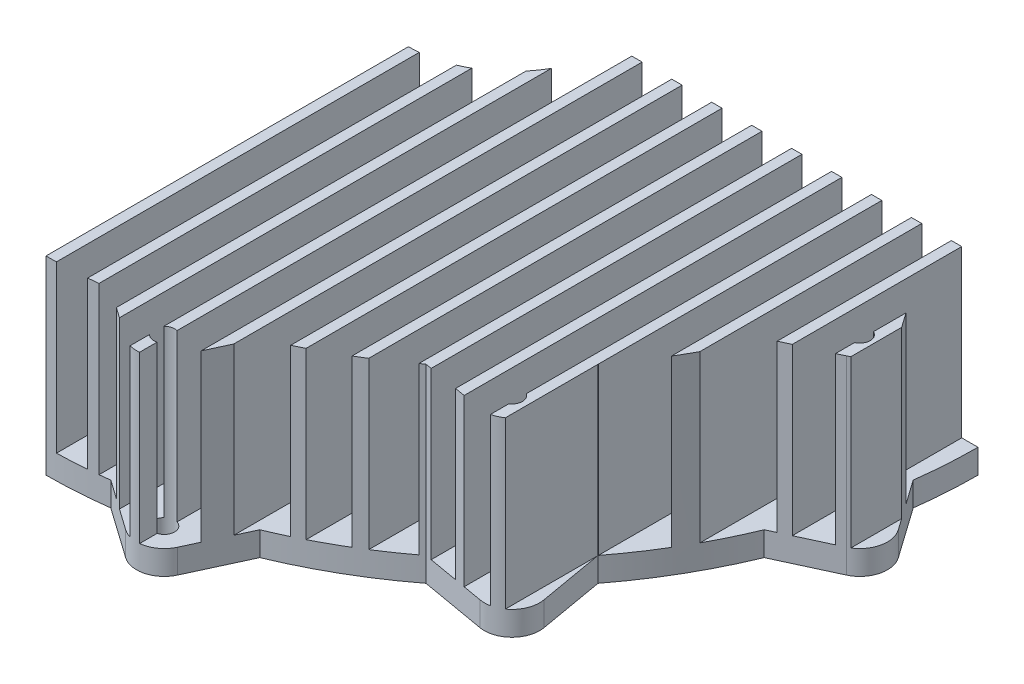
SolidWorks part; units mm, degrees
ref_plane "Ön Düzlem" through (0, 0, 0) normal (0, 0, 1) x (1, 0, 0)
ref_plane "Üst Düzlem" through (0, 0, 0) normal (0, 1, 0) x (1, 0, 0)
ref_plane "Sağ Düzlem" through (0, 0, 0) normal (1, 0, 0) x (0, 0, -1)
sketch "Sketch1" plane through (0, 0, 0) normal (0, 0, 1) x (1, 0, 0)
  line L0 (11.5714, 7) -> (11.5714, 55)
  line L1 (0, 0) -> (165, 0)
  line L2 (0, 0) -> (0, 7)
  line L3 (3, 7) -> (11.5714, 7)
  line L4 (165, 0) -> (165, 10)
  line L6 (0, 7) -> (0, 55)
  line L7 (0, 55) -> (3, 55)
  line L8 (3, 7) -> (3, 55)
  line L10 (14.5714, 7) -> (14.5714, 55)
  line L11 (11.5714, 55) -> (14.5714, 55)
  line L12 (23.1429, 7) -> (23.1429, 55)
  line L14 (26.1429, 7) -> (26.1429, 55)
  line L15 (23.1429, 55) -> (26.1429, 55)
  line L16 (34.7143, 7) -> (34.7143, 55)
  line L18 (37.7143, 7) -> (37.7143, 55)
  line L19 (34.7143, 55) -> (37.7143, 55)
  line L20 (46.2857, 7) -> (46.2857, 55)
  line L22 (49.2857, 7) -> (49.2857, 55)
  line L23 (46.2857, 55) -> (49.2857, 55)
  line L24 (57.8571, 7) -> (57.8571, 55)
  line L26 (60.8571, 7) -> (60.8571, 55)
  line L27 (57.8571, 55) -> (60.8571, 55)
  line L28 (69.4286, 7) -> (69.4286, 55)
  line L30 (72.4286, 7) -> (72.4286, 55)
  line L31 (69.4286, 55) -> (72.4286, 55)
  line L32 (81, 7) -> (81, 55)
  line L34 (84, 7) -> (84, 55)
  line L35 (81, 55) -> (84, 55)
  line L36 (92.5714, 7) -> (92.5714, 55)
  line L38 (95.5714, 7) -> (95.5714, 55)
  line L39 (92.5714, 55) -> (95.5714, 55)
  line L40 (104.1429, 7) -> (104.1429, 55)
  line L42 (107.1429, 7) -> (107.1429, 55)
  line L43 (104.1429, 55) -> (107.1429, 55)
  line L44 (115.7143, 7) -> (115.7143, 55)
  line L46 (118.7143, 7) -> (118.7143, 55)
  line L47 (115.7143, 55) -> (118.7143, 55)
  line L48 (127.2857, 7) -> (127.2857, 55)
  line L50 (130.2857, 7) -> (130.2857, 55)
  line L51 (127.2857, 55) -> (130.2857, 55)
  line L52 (138.8571, 7) -> (138.8571, 55)
  line L54 (141.8571, 7) -> (141.8571, 55)
  line L55 (138.8571, 55) -> (141.8571, 55)
  line L56 (150.4286, 7) -> (150.4286, 55)
  line L58 (153.4286, 7) -> (153.4286, 55)
  line L59 (150.4286, 55) -> (153.4286, 55)
  line L60 (162, 7) -> (162, 55)
  line L62 (165, 7) -> (165, 55)
  line L63 (162, 55) -> (165, 55)
  line L78 (14.5714, 7) -> (23.1429, 7)
  line L79 (26.1429, 7) -> (34.7143, 7)
  line L80 (37.7143, 7) -> (46.2857, 7)
  line L81 (49.2857, 7) -> (57.8571, 7)
  line L82 (60.8571, 7) -> (69.4286, 7)
  line L83 (72.4286, 7) -> (81, 7)
  line L84 (84, 7) -> (92.5714, 7)
  line L85 (95.5714, 7) -> (104.1429, 7)
  line L86 (107.1429, 7) -> (115.7143, 7)
  line L87 (118.7143, 7) -> (127.2857, 7)
  line L88 (130.2857, 7) -> (138.8571, 7)
  line L89 (141.8571, 7) -> (150.4286, 7)
  line L90 (153.4286, 7) -> (162, 7)
  dimension "D1" = 165
  dimension "D2" = 7
  dimension "D3" = 48
  dimension "D4" = 3
  dimension "D5" = 15
extrude "Boss-Extrude1" add sketch "Sketch1" along normal blind 1000 contours L90 L58 L59 L56 L89 L54 L55 L52 L88 L50 L51 L48 L87 L46 L47 L44 L86 L42 L43 L40 L85 L38 L39 L36 L84 L34 L35 L32 L83 L30 L31 L28 L82 L26 L27 L24 L81 L22 L23 L20 L80 L18 L19 L16 L79 L14 L15 L12 L78 L10 L11
sketch "Sketch2" plane through (0, 0, 0) normal (0, -1, 0) x (1, 0, 0)
  line L0 (0, 142.5) -> (0, 0)
  line L1 (0, 0) -> (142.5, 0)
  line L2 (0, 0) -> (102.5305, 102.5305) construction
  line L3 (0, 0) -> (36.8817, 137.6444) construction
  line L4 (0, 0) -> (137.6444, 36.8817) construction
  line L5 (0, 0) -> (17.621, 133.8451)
  line L6 (0, 0) -> (51.6623, 124.7237)
  line L7 (0, 0) -> (82.1828, 107.1027)
  line L8 (0, 0) -> (107.1027, 82.1828)
  line L9 (0, 0) -> (124.7237, 51.6623)
  line L10 (0, 0) -> (133.8451, 17.621)
  line L11 (17.621, 133.8451) -> (32.2695, 144.181)
  line L12 (51.6623, 124.7237) -> (44.1443, 140.9992)
  line L13 (82.1828, 107.1027) -> (101.1561, 110.4115)
  line L14 (107.1027, 82.1828) -> (110.4115, 101.1561)
  line L15 (124.7237, 51.6623) -> (140.9992, 44.1443)
  line L16 (133.8451, 17.621) -> (144.181, 32.2695)
  arc A0 (135, 0) -> (133.8451, 17.621) centre (0, 0) ccw
  circle A2 centre (36.8817, 137.6444) radius 3
  circle A3 centre (102.5305, 102.5305) radius 3
  circle A4 centre (137.6444, 36.8817) radius 3
  arc A5 (44.1443, 140.9992) -> (32.2695, 144.181) centre (36.8817, 137.6444) ccw
  arc A6 (110.4115, 101.1561) -> (101.1561, 110.4115) centre (102.5305, 102.5305) ccw
  arc A7 (144.181, 32.2695) -> (140.9992, 44.1443) centre (137.6444, 36.8817) ccw
  arc A9 (101.9184, 99.5936) -> (99.5936, 101.9184) centre (0, 0) ccw
  arc A12 (138.3903, 33.9759) -> (136.8375, 39.7712) centre (0, 0) ccw
  arc A13 (17.621, 133.8451) -> (0, 135) centre (0, 0) ccw
  arc A14 (82.1828, 107.1027) -> (51.6623, 124.7237) centre (0, 0) ccw
  arc A15 (124.7237, 51.6623) -> (107.1027, 82.1828) centre (0, 0) ccw
  dimension "D1" = 270
  dimension "D3" = 6
  dimension "D4" = 6
  dimension "D5" = 6
  dimension "D8" = 16
  dimension "D9" = 16
  dimension "D10" = 16
  dimension "D6" = 15
  dimension "D7" = 15
  dimension "D11" = 45
  dimension "D12" = 7.5
  dimension "D13" = 7.5
  dimension "D14" = 7.5
  dimension "D15" = 7.5
  dimension "D16" = 7.5
  dimension "D17" = 7.5
extrude "Cut-Extrude2" cut sketch "Sketch2" against normal through all
sketch "Sketch3" plane through (0, 55, 0) normal (0, 1, 0) x (1, 0, 0)
  circle A0 centre (0, 0) radius 30
  dimension "D1" = 60
extrude "Cut-Extrude3" cut sketch "Sketch3" against normal blind 67
